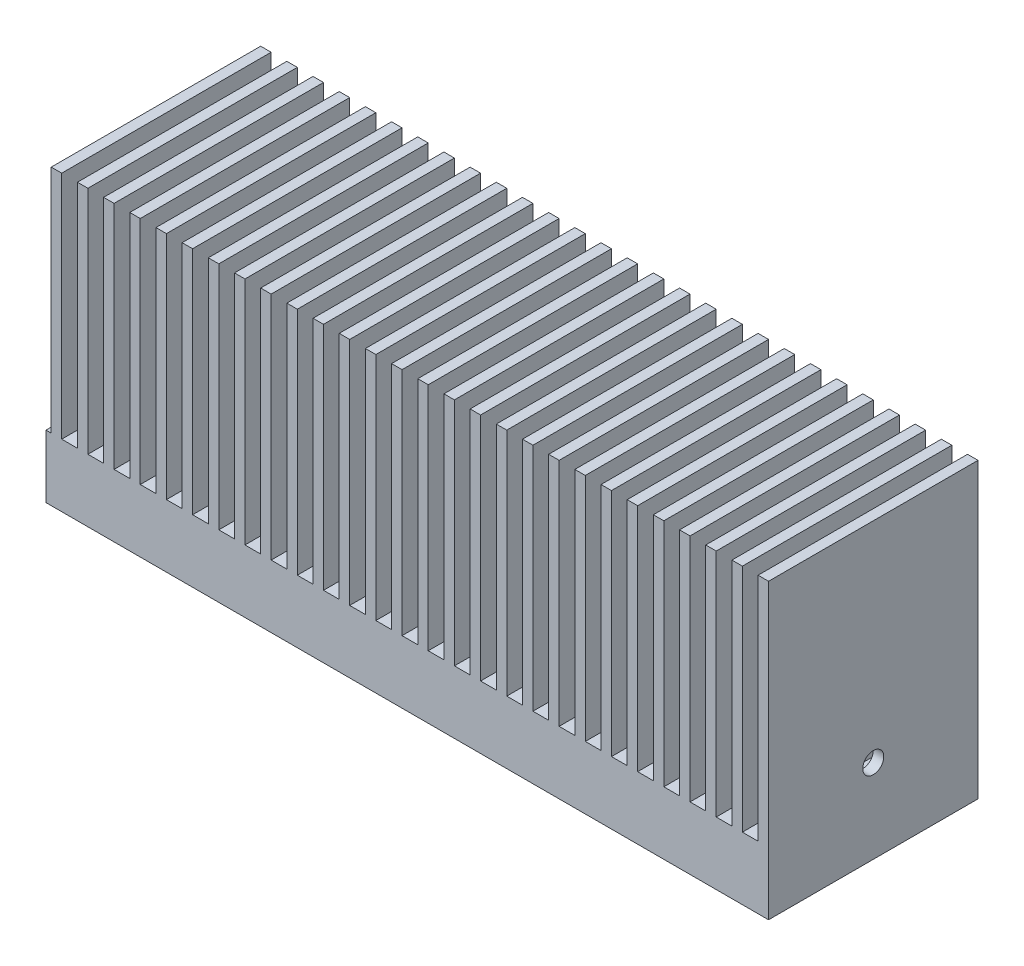
SolidWorks part; units mm, degrees
ref_plane "前视基准面" through (0, 0, 0) normal (0, 0, 1) x (1, 0, 0)
ref_plane "上视基准面" through (0, 0, 0) normal (0, 1, 0) x (1, 0, 0)
ref_plane "右视基准面" through (0, 0, 0) normal (1, 0, 0) x (0, 0, -1)
sketch "草图1" plane through (0, 0, 0) normal (0, 1, 0) x (1, 0, 0)
  line L0 (-38.2837, 0) -> (40.4297, 0) construction
  line L1 (-34.5, 10) -> (34.5, 10)
  line L2 (-34.5, 10) -> (-34.5, -10)
  line L3 (-34.5, -10) -> (34.5, -10)
  line L4 (34.5, 10) -> (34.5, -10)
  line L5 (0, 27.2258) -> (0, -28.9127) construction
  dimension "D1" = 69
  dimension "D2" = 20
extrude "拉伸1" add sketch "草图1" along normal blind 28
sketch "草图2" plane through (0, 28, 0) normal (0, 1, 0) x (-1, 0, 0)
  line L0 (1, -20.8895) -> (1, 19.2743) construction
  line L1 (-34.5, -10) -> (34.5, -10) construction
  line L2 (-1, -10) -> (0.5, -10)
  line L3 (-1, -10) -> (-1, 10)
  line L4 (-1, 10) -> (0.5, 10)
  line L5 (0.5, -10) -> (0.5, 10)
  line L6 (34.5, 10) -> (-34.5, 10) construction
  line L7 (1.5, -10) -> (3, -10)
  line L8 (1.5, -10) -> (1.5, 10)
  line L9 (1.5, 10) -> (3, 10)
  line L10 (3, -10) -> (3, 10)
  line L11 (4, -10) -> (5.5, -10)
  line L12 (4, -10) -> (4, 10)
  line L13 (4, 10) -> (5.5, 10)
  line L14 (5.5, -10) -> (5.5, 10)
  line L15 (6.5, -10) -> (8, -10)
  line L16 (6.5, -10) -> (6.5, 10)
  line L17 (6.5, 10) -> (8, 10)
  line L18 (8, -10) -> (8, 10)
  line L19 (9, -10) -> (10.5, -10)
  line L20 (9, -10) -> (9, 10)
  line L21 (9, 10) -> (10.5, 10)
  line L22 (10.5, -10) -> (10.5, 10)
  line L23 (11.5, -10) -> (13, -10)
  line L24 (11.5, -10) -> (11.5, 10)
  line L25 (11.5, 10) -> (13, 10)
  line L26 (13, -10) -> (13, 10)
  line L27 (14, -10) -> (15.5, -10)
  line L28 (14, -10) -> (14, 10)
  line L29 (14, 10) -> (15.5, 10)
  line L30 (15.5, -10) -> (15.5, 10)
  line L31 (16.5, -10) -> (18, -10)
  line L32 (16.5, -10) -> (16.5, 10)
  line L33 (16.5, 10) -> (18, 10)
  line L34 (18, -10) -> (18, 10)
  line L35 (19, -10) -> (20.5, -10)
  line L36 (19, -10) -> (19, 10)
  line L37 (19, 10) -> (20.5, 10)
  line L38 (20.5, -10) -> (20.5, 10)
  line L39 (21.5, -10) -> (23, -10)
  line L40 (21.5, -10) -> (21.5, 10)
  line L41 (21.5, 10) -> (23, 10)
  line L42 (23, -10) -> (23, 10)
  line L43 (24, -10) -> (25.5, -10)
  line L44 (24, -10) -> (24, 10)
  line L45 (24, 10) -> (25.5, 10)
  line L46 (25.5, -10) -> (25.5, 10)
  line L47 (26.5, -10) -> (28, -10)
  line L48 (26.5, -10) -> (26.5, 10)
  line L49 (26.5, 10) -> (28, 10)
  line L50 (28, -10) -> (28, 10)
  line L51 (29, -10) -> (30.5, -10)
  line L52 (29, -10) -> (29, 10)
  line L53 (29, 10) -> (30.5, 10)
  line L54 (30.5, -10) -> (30.5, 10)
  line L55 (31.5, -10) -> (33, -10)
  line L56 (31.5, -10) -> (31.5, 10)
  line L57 (31.5, 10) -> (33, 10)
  line L58 (33, -10) -> (33, 10)
  line L59 (34, -10) -> (35.5, -10)
  line L60 (34, -10) -> (34, 10)
  line L61 (34, 10) -> (35.5, 10)
  line L62 (35.5, -10) -> (35.5, 10)
  line L63 (-3.5, -10) -> (-2, -10)
  line L64 (-3.5, -10) -> (-3.5, 10)
  line L65 (-3.5, 10) -> (-2, 10)
  line L66 (-2, -10) -> (-2, 10)
  line L67 (-6, -10) -> (-4.5, -10)
  line L68 (-6, -10) -> (-6, 10)
  line L69 (-6, 10) -> (-4.5, 10)
  line L70 (-4.5, -10) -> (-4.5, 10)
  line L71 (-8.5, -10) -> (-7, -10)
  line L72 (-8.5, -10) -> (-8.5, 10)
  line L73 (-8.5, 10) -> (-7, 10)
  line L74 (-7, -10) -> (-7, 10)
  line L75 (-11, -10) -> (-9.5, -10)
  line L76 (-11, -10) -> (-11, 10)
  line L77 (-11, 10) -> (-9.5, 10)
  line L78 (-9.5, -10) -> (-9.5, 10)
  line L79 (-13.5, -10) -> (-12, -10)
  line L80 (-13.5, -10) -> (-13.5, 10)
  line L81 (-13.5, 10) -> (-12, 10)
  line L82 (-12, -10) -> (-12, 10)
  line L83 (-16, -10) -> (-14.5, -10)
  line L84 (-16, -10) -> (-16, 10)
  line L85 (-16, 10) -> (-14.5, 10)
  line L86 (-14.5, -10) -> (-14.5, 10)
  line L87 (-18.5, -10) -> (-17, -10)
  line L88 (-18.5, -10) -> (-18.5, 10)
  line L89 (-18.5, 10) -> (-17, 10)
  line L90 (-17, -10) -> (-17, 10)
  line L91 (-21, -10) -> (-19.5, -10)
  line L92 (-21, -10) -> (-21, 10)
  line L93 (-21, 10) -> (-19.5, 10)
  line L94 (-19.5, -10) -> (-19.5, 10)
  line L95 (-23.5, -10) -> (-22, -10)
  line L96 (-23.5, -10) -> (-23.5, 10)
  line L97 (-23.5, 10) -> (-22, 10)
  line L98 (-22, -10) -> (-22, 10)
  line L99 (-26, -10) -> (-24.5, -10)
  line L100 (-26, -10) -> (-26, 10)
  line L101 (-26, 10) -> (-24.5, 10)
  line L102 (-24.5, -10) -> (-24.5, 10)
  line L103 (-28.5, -10) -> (-27, -10)
  line L104 (-28.5, -10) -> (-28.5, 10)
  line L105 (-28.5, 10) -> (-27, 10)
  line L106 (-27, -10) -> (-27, 10)
  line L107 (-31, -10) -> (-29.5, -10)
  line L108 (-31, -10) -> (-31, 10)
  line L109 (-31, 10) -> (-29.5, 10)
  line L110 (-29.5, -10) -> (-29.5, 10)
  line L111 (-33.5, -10) -> (-32, -10)
  line L112 (-33.5, -10) -> (-33.5, 10)
  line L113 (-33.5, 10) -> (-32, 10)
  line L114 (-32, -10) -> (-32, 10)
  dimension "D1" = 1.5
  dimension "D2" = 0.5
  dimension "D3" = 1
extrude "切除-拉伸1" cut sketch "草图2" against normal offset from surface (22 mm away) 6 up to face at (0, 0, 0)
sketch "草图3" plane through (-34, 0, 0) normal (-1, 0, 0) x (0, 0, 1)
  line L0 (0, -2.6217) -> (0, 30.0974) construction
  line L1 (-10, 6) -> (10, 6) construction
  circle A0 centre (0, 8) radius 1
  dimension "D1" = 2
  dimension "D2" = 2
extrude "切除-拉伸2" cut sketch "草图3" against normal blind 5
sketch "草图4" plane through (34.5, 0, 0) normal (1, 0, 0) x (0, 0, -1)
  line L0 (0, -4.4989) -> (0, 30.9888) construction
  circle A0 centre (0, 8) radius 1 construction
  circle A1 centre (0, 8) radius 1
extrude "切除-拉伸3" cut sketch "草图4" against normal blind 5
